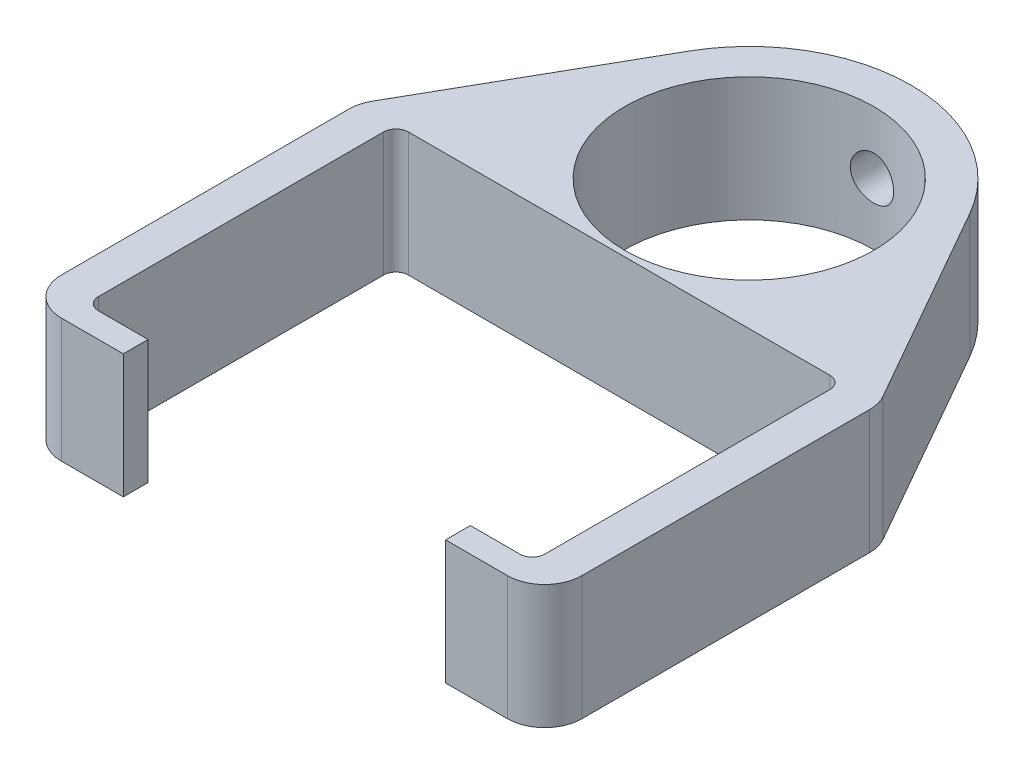
SolidWorks part; units mm, degrees
ref_plane "前视基准面" through (0, 0, 0) normal (0, 0, 1) x (1, 0, 0)
ref_plane "上视基准面" through (0, 0, 0) normal (0, 1, 0) x (1, 0, 0)
ref_plane "右视基准面" through (0, 0, 0) normal (1, 0, 0) x (0, 0, -1)
sketch "草图1" plane through (0, 0, 0) normal (0, 1, 0) x (1, 0, 0)
  line L0 (-21, -10.5) -> (21, -10.5)
  line L1 (0, -21) -> (0, 0) construction
  line L2 (-21, -10.5) -> (-11.3393, 6.4593)
  line L3 (21, -10.5) -> (11.3393, 6.4593)
  line L5 (-21, -10.5) -> (-18, -10.5)
  line L6 (-21, -10.5) -> (-21, -37.5)
  line L7 (-21, -37.5) -> (-18, -37.5)
  line L8 (-18, -10.5) -> (-18, -37.5)
  line L9 (21, -10.5) -> (18, -10.5)
  line L10 (21, -10.5) -> (21, -37.5)
  line L11 (21, -37.5) -> (18, -37.5)
  line L12 (18, -10.5) -> (18, -37.5)
  line L13 (-18, -37.5) -> (-13, -37.5)
  line L14 (-18, -37.5) -> (-18, -35.5)
  line L15 (-18, -35.5) -> (-13, -35.5)
  line L16 (-13, -37.5) -> (-13, -35.5)
  line L17 (18, -37.5) -> (13, -37.5)
  line L18 (18, -37.5) -> (18, -35.5)
  line L19 (18, -35.5) -> (13, -35.5)
  line L20 (13, -37.5) -> (13, -35.5)
  circle A0 centre (0, 0) radius 10.05
  arc A1 (7.7494, -10.5) -> (-7.7494, -10.5) centre (0, 0) ccw
  point P10 (0, -10.5)
  point P22 (0, 0)
  dimension "D1" = 20.1
  dimension "D2" = 3
  dimension "D3" = 42
  dimension "D4" = 10.5
  dimension "D5" = 3
  dimension "D6" = 27
  dimension "D7" = 2
  dimension "D8" = 5
extrude "凸台-拉伸1" add sketch "草图1" along normal blind 10
fillet "圆角1" radius 3 4 edges at (21, 5, 37.5) (-21, 5, 37.5) (21, 5, 10.5) (-21, 5, 10.5)
fillet "圆角2" radius 1 4 edges at (18, 5, 35.5) (18, 5, 10.5) (-18, 5, 35.5) (-18, 5, 10.5)
sketch "草图2" plane through (0, 0, 0) normal (0, 0, 1) x (1, 0, 0)
  line L0 (0, 5) -> (0, 0) construction
  circle A0 centre (0, 5) radius 1.75
  dimension "D2" = 3.5
  dimension "D1" = 5
extrude "切除-拉伸1" cut sketch "草图2" against normal through all
